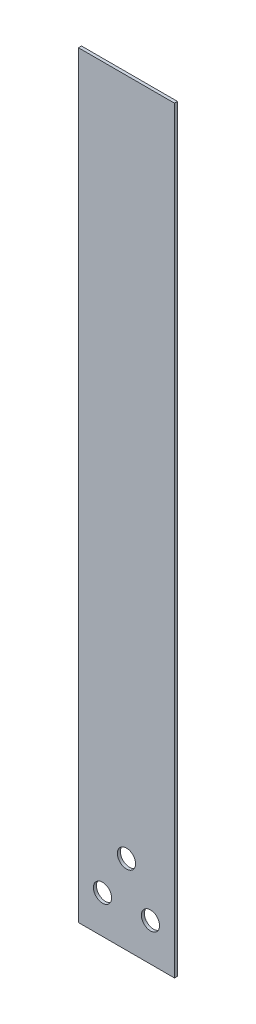
SolidWorks part; units mm, degrees
ref_plane "Спереди" through (0, 0, 0) normal (0, 0, 1) x (1, 0, 0)
ref_plane "Сверху" through (0, 0, 0) normal (0, 1, 0) x (1, 0, 0)
ref_plane "Справа" through (0, 0, 0) normal (1, 0, 0) x (0, 0, -1)
sketch "Эскиз1" plane through (0, 0, 0) normal (0, 0, 1) x (1, 0, 0)
  line L1 (-19, 150) -> (19, 150)
  line L2 (-19, 150) -> (-19, -150)
  line L3 (-19, -150) -> (19, -150)
  line L4 (19, 150) -> (19, -150)
  line L5 (-19, 150) -> (19, -150) construction
  line L6 (-19, -150) -> (19, 150) construction
  point P0 (0, 0)
  dimension "D1" = 38
  dimension "D2" = 300
extrude "Бобышка-Вытянуть1" add sketch "Эскиз1" along normal blind 1.2
sketch "Эскиз2" plane through (0, 0, 1.2) normal (0, 0, 1) x (1, 0, 0)
  line L0 (-19, -135) -> (19, -135)
  line L1 (-19, 150) -> (-19, -150) construction
  line L2 (19, -150) -> (19, 150) construction
  line L3 (0, -150) -> (0, -98.1411)
  line L4 (-19, -150) -> (19, -150) construction
  circle A0 centre (-9.5, -135) radius 3.6
  circle A1 centre (9.5, -135) radius 3.6
  circle A2 centre (0, -118.5455) radius 3.6
  point P17 (0, 0)
  dimension "D2" = 7.2
  dimension "D3" = 7.2
  dimension "D4" = 7.2
  dimension "D6" = 9.5
  dimension "D7" = 19
  dimension "D1" = 15
  dimension "D5" = 9.5
extrude "Вырез-Вытянуть1" cut sketch "Эскиз2" against normal blind 1.2 contours L3 A2 | L3 A2 | L0 A0 | L0 A0 | L0 A1
